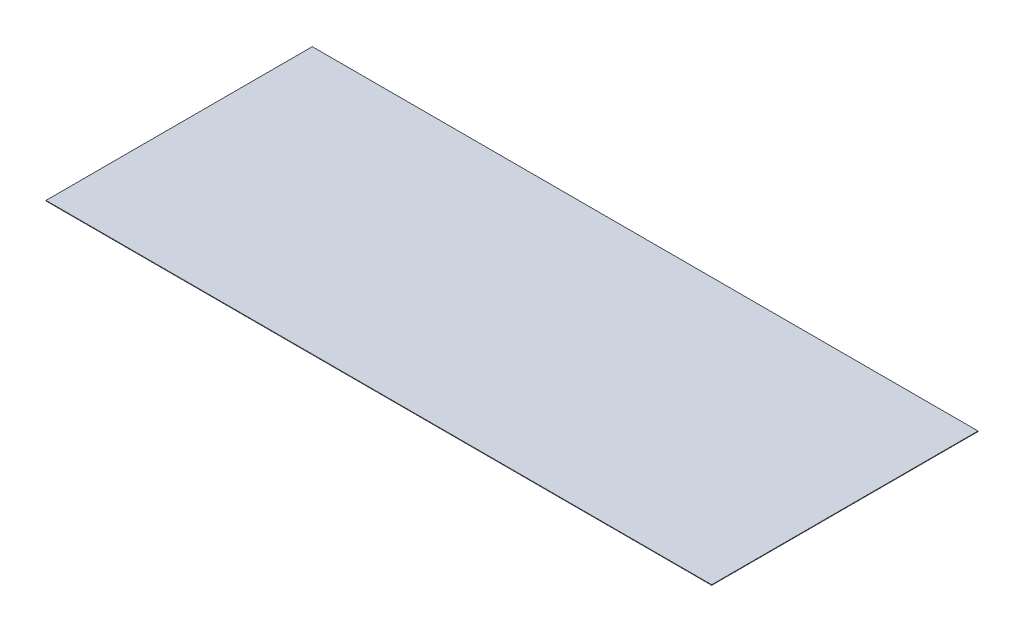
SolidWorks part; units mm, degrees
material "Perspex (TM) GS Acrylic Cast Sheet"
ref_plane "Front Plane" through (0, 0, 0) normal (0, 0, 1) x (1, 0, 0)
ref_plane "Top Plane" through (0, 0, 0) normal (0, 1, 0) x (1, 0, 0)
ref_plane "Right Plane" through (0, 0, 0) normal (1, 0, 0) x (0, 0, -1)
sketch "Sketch1" plane through (0, 0, 0) normal (0, 1, 0) x (1, 0, 0)
  line L1 (-125, 50) -> (125, 50)
  line L2 (-125, 50) -> (-125, -50)
  line L3 (-125, -50) -> (125, -50)
  line L4 (125, 50) -> (125, -50)
  line L5 (-125, 50) -> (125, -50) construction
  line L6 (-125, -50) -> (125, 50) construction
  point P0 (0, 0)
  dimension "D1" = 250
  dimension "D2" = 100
extrude "Boss-Extrude1" add sketch "Sketch1" along normal blind 0.2
